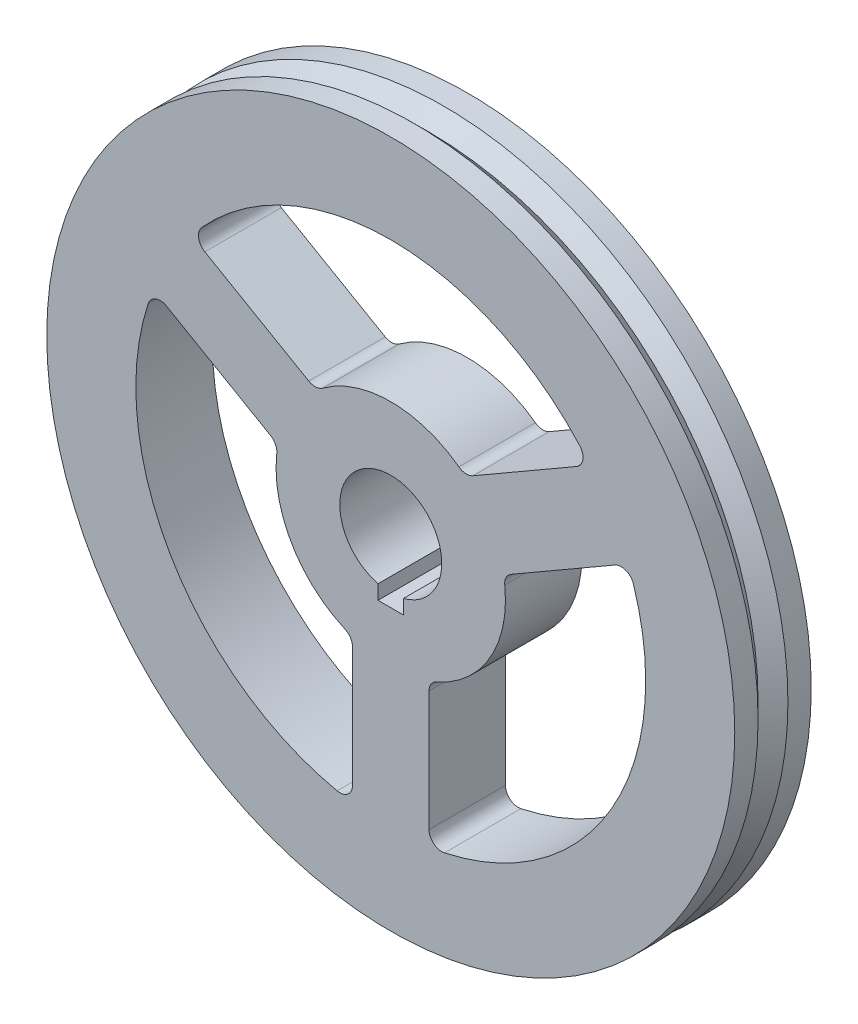
SolidWorks part; units mm, degrees
ref_plane "Front Plane" through (0, 0, 0) normal (0, 0, 1) x (1, 0, 0)
ref_plane "Top Plane" through (0, 0, 0) normal (0, 1, 0) x (1, 0, 0)
ref_plane "Right Plane" through (0, 0, 0) normal (1, 0, 0) x (0, 0, -1)
sketch "Sketch1" plane through (0, 0, 0) normal (0, 0, 1) x (1, 0, 0)
  line L0 (0, 108.1587) -> (0, -129.6601) construction
  line L1 (-123.7961, 0) -> (132.2663, 0) construction
  line L2 (-15, -45.8258) -> (-15, -92.8709)
  line L3 (15, -45.8258) -> (15, -92.8709)
  line L4 (-32.1863, 35.9033) -> (-72.9285, 59.4258)
  line L5 (-47.1863, 9.9225) -> (-87.9285, 33.4451)
  line L6 (47.1863, 9.9225) -> (87.9285, 33.4451)
  line L7 (32.1863, 35.9033) -> (72.9285, 59.4258)
  circle A0 centre (0, 0) radius 125
  arc A1 (-44.7176, 5.0331) -> (-18, -41.2432) centre (0, 0) ccw
  circle A2 centre (0, 0) radius 20
  arc A3 (-95.1879, 30.6473) -> (-21.0526, -97.7588) centre (0, 0) ccw
  arc A4 (-21.0526, -97.7588) -> (-15, -92.8709) centre (-20, -92.8709) ccw
  arc A5 (-18, -41.2432) -> (-15, -45.8258) centre (-20, -45.8258) cw
  arc A6 (21.0526, -97.7588) -> (15, -92.8709) centre (20, -92.8709) cw
  arc A7 (18, -41.2432) -> (15, -45.8258) centre (20, -45.8258) ccw
  arc A8 (-44.7176, 5.0331) -> (-47.1863, 9.9225) centre (-49.6863, 5.5924) ccw
  arc A9 (-26.7176, 36.21) -> (-32.1863, 35.9033) centre (-29.6863, 40.2334) cw
  arc A10 (-95.1879, 30.6473) -> (-87.9285, 33.4451) centre (-90.4285, 29.1149) cw
  arc A11 (-74.1353, 67.1115) -> (-72.9285, 59.4258) centre (-70.4285, 63.7559) ccw
  arc A12 (26.7176, 36.21) -> (32.1863, 35.9033) centre (29.6863, 40.2334) ccw
  arc A13 (44.7176, 5.0331) -> (47.1863, 9.9225) centre (49.6863, 5.5924) cw
  arc A14 (74.1353, 67.1115) -> (72.9285, 59.4258) centre (70.4285, 63.7559) cw
  arc A15 (95.1879, 30.6473) -> (87.9285, 33.4451) centre (90.4285, 29.1149) ccw
  arc A16 (26.7176, 36.21) -> (-26.7176, 36.21) centre (0, 0) ccw
  arc A17 (74.1353, 67.1115) -> (-74.1353, 67.1115) centre (0, 0) ccw
  arc A18 (21.0526, -97.7588) -> (95.1879, 30.6473) centre (0, 0) ccw
  arc A19 (18, -41.2432) -> (44.7176, 5.0331) centre (0, 0) ccw
  point P26 (0, 0)
  point P50 (0, 0)
  dimension "D1" = 45
  dimension "D2" = 250
  dimension "D3" = 200
  dimension "D4" = 40
  dimension "D9" = 5
  dimension "D10" = 5
  dimension "D11" = 5
  dimension "D5" = 3
  dimension "D6" = 15
extrude "Boss-Extrude1" add sketch "Sketch1" along normal blind 30
sketch "Sketch2" plane through (0, 0, 30) normal (0, 0, 1) x (1, 0, 0)
  line L1 (-5, -15) -> (5, -15)
  line L2 (-5, -15) -> (-5, -25)
  line L3 (-5, -25) -> (5, -25)
  line L4 (5, -15) -> (5, -25)
  line L5 (-5, -15) -> (5, -25) construction
  line L6 (-5, -25) -> (5, -15) construction
  circle A0 centre (0, 0) radius 20 construction
  point P0 (0, -20)
  dimension "D1" = 5
  dimension "D2" = 10
extrude "Cut-Extrude1" cut sketch "Sketch2" against normal up to next
ref_plane "Plane1" through (0, 0, 0) normal (1, 0, 0) x (0, 0, -1)
sketch "Sketch3" plane through (0, 0, 0) normal (1, 0, 0) x (0, 0, -1)
  line L0 (-30, 124.9461) -> (-25, 124.9461)
  line L2 (-30, 125) -> (-30, -125) construction
  line L3 (0, 124.9461) -> (-5, 124.9461)
  line L6 (0, -125) -> (0, 125) construction
  line L7 (-15, 125) -> (-15, 114.9461) construction
  line L8 (0, 125) -> (-30, 125) construction
  line L9 (-25, 124.9461) -> (-15, 114.9461)
  line L10 (-15, 114.9461) -> (-5, 124.9461)
  line L11 (10.8718, 0) -> (-51.1449, 0) construction
  dimension "D1" = 5
  dimension "D2" = 5
  dimension "D3" = 10
revolve "Revolve-Thin1" add sketch "Sketch3" angle 360 about L11 wall 10
